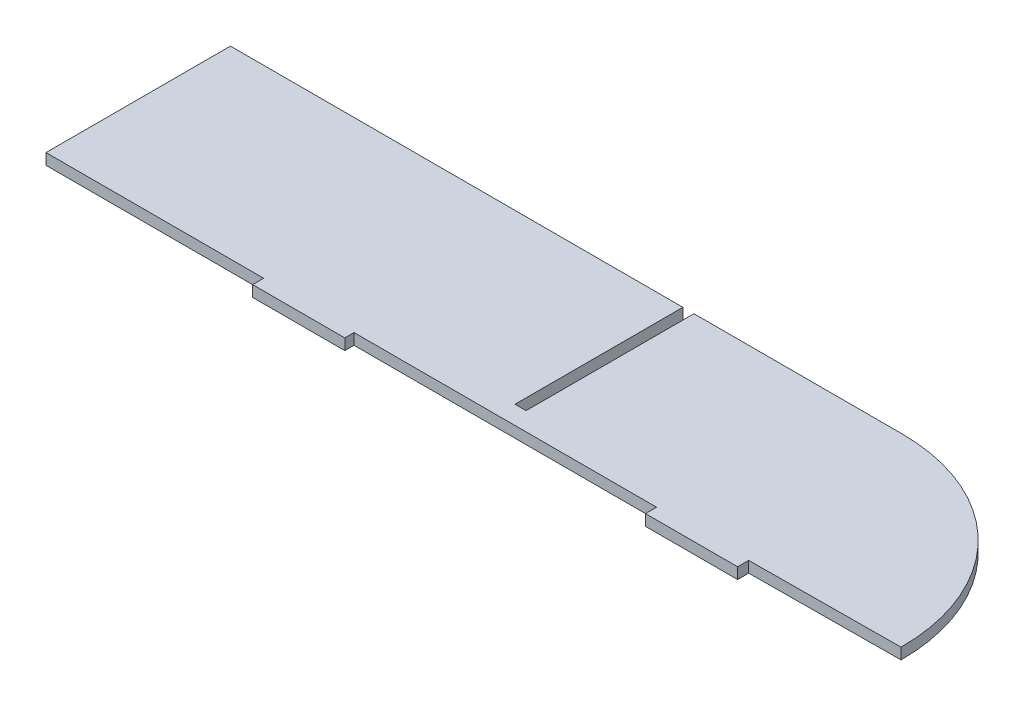
SolidWorks part; units mm, degrees
material "Maple"
ref_plane "Front Plane" through (0, 0, 0) normal (0, 0, 1) x (1, 0, 0)
ref_plane "Top Plane" through (0, 0, 0) normal (0, 1, 0) x (1, 0, 0)
ref_plane "Right Plane" through (0, 0, 0) normal (1, 0, 0) x (0, 0, -1)
sketch "Sketch1" plane through (0, 0, 0) normal (0, 1, 0) x (1, 0, 0)
  line L1 (-232, -140.0402) -> (13.3161, -140.0402)
  line L2 (-232, -140.0402) -> (-232, -240.0402)
  line L3 (-232, -240.0402) -> (-114, -240.0402)
  line L7 (13.3161, -231.0402) -> (19.3161, -231.0402)
  line L8 (13.3161, -231.0402) -> (13.3161, -140.0402)
  line L13 (-289.5, 225) -> (-289.5, -457) construction
  line L18 (19.3161, -231.0402) -> (19.3161, -140.0402)
  line L19 (150, -247.0402) -> (100, -247.0402)
  line L21 (-114, -240.0402) -> (-114, -246.0402)
  line L22 (-114, -246.0402) -> (-64, -246.0402)
  line L23 (-64, -241.0402) -> (-64, -246.0402)
  line L24 (149.9586, -241.0404) -> (231.9991, -240.4746)
  line L26 (100, -241.0402) -> (100, -247.0402)
  line L28 (149.9586, -241.0404) -> (150, -247.0402)
  line L29 (-64, -241.0402) -> (100, -241.0402)
  line L30 (19.3161, -140.0402) -> (132, -140.0402)
  arc A0 (231.9991, -240.4746) -> (132, -140.0402) centre (132, -240.0402) ccw
  point P0 (0, 0)
  point P4 (0, 0)
  dimension "D3" = 100
  dimension "D2" = 100
  dimension "D4" = 50
  dimension "D5" = 10
  dimension "D6" = 91
  dimension "D7" = 6
  dimension "D8" = 6
  dimension "D9" = 57.5
  dimension "D10" = 6
  dimension "D11" = 118
  dimension "D12" = 50
  dimension "D13" = 6
  dimension "D14" = 90
  dimension "D15" = 90
  dimension "D16" = 90
extrude "Boss-Extrude1" add sketch "Sketch1" along normal blind 6
